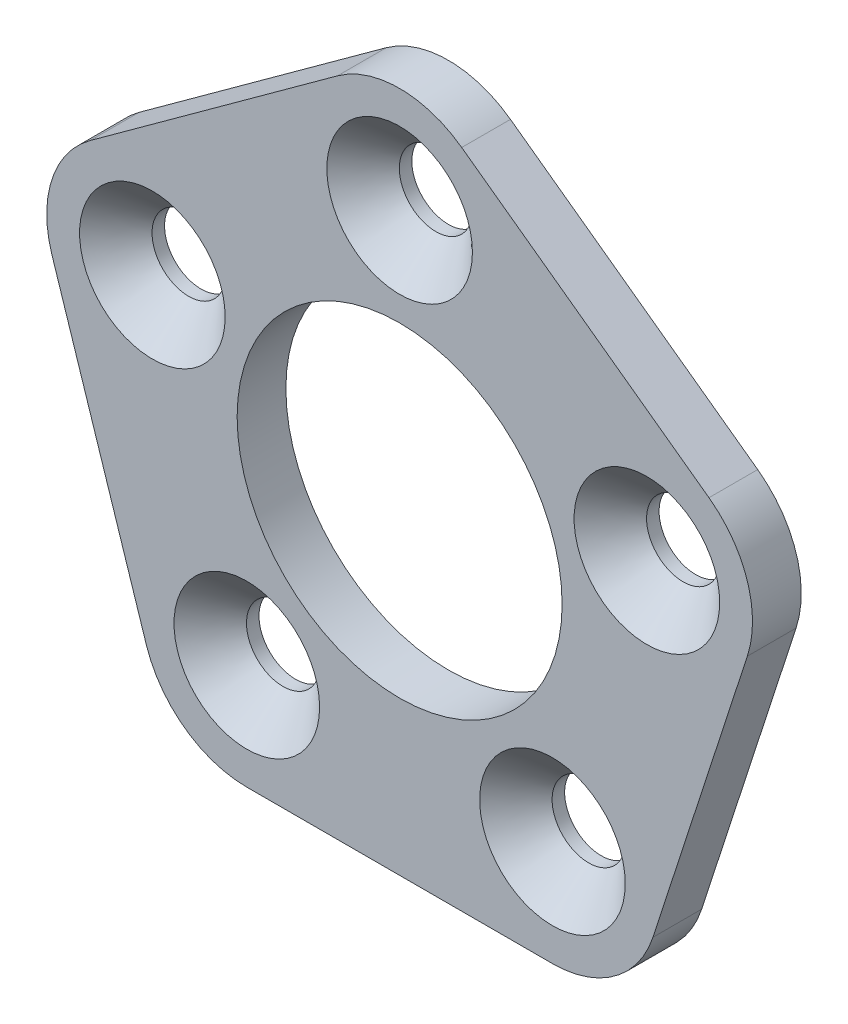
SolidWorks part; units mm, degrees
material "AISI Type A2 Tool Steel"
ref_plane "Front" through (0, 0, 0) normal (0, 0, 1) x (1, 0, 0)
ref_plane "Top" through (0, 0, 0) normal (0, 1, 0) x (1, 0, 0)
ref_plane "Right" through (0, 0, 0) normal (1, 0, 0) x (0, 0, -1)
sketch "Sketch1" plane through (0, 0, 0) normal (0, 0, 1) x (1, 0, 0)
  line L0 (-21.3988, 2.9357) -> (-15.5864, -14.9529)
  line L1 (-19.0375, 10.2029) -> (-3.8206, 21.2586)
  line L2 (-9.4046, -19.4443) -> (9.4046, -19.4443)
  line L3 (15.5864, -14.9529) -> (21.3988, 2.9357)
  line L4 (3.8206, 21.2586) -> (19.0375, 10.2029)
  circle A0 centre (0, 0) radius 16 construction
  circle A1 centre (0, 0) radius 19 construction
  circle A2 centre (0, 0) radius 10
  arc A3 (3.8206, 21.2586) -> (-3.8206, 21.2586) centre (0, 16) ccw
  arc A4 (21.3988, 2.9357) -> (19.0375, 10.2029) centre (15.2169, 4.9443) ccw
  arc A5 (9.4046, -19.4443) -> (15.5864, -14.9529) centre (9.4046, -12.9443) ccw
  arc A6 (-15.5864, -14.9529) -> (-9.4046, -19.4443) centre (-9.4046, -12.9443) ccw
  arc A7 (-19.0375, 10.2029) -> (-21.3988, 2.9357) centre (-15.2169, 4.9443) ccw
  arc A8 (-6.3645, 14.6797) -> (6.3645, 14.6797) centre (0, 16) ccw construction
  arc A9 (-15.9279, -1.5167) -> (-11.9945, 10.5893) centre (-15.2169, 4.9443) ccw construction
  arc A10 (-3.4795, -15.6171) -> (-13.7775, -8.1352) centre (-9.4046, -12.9443) ccw construction
  arc A11 (13.7775, -8.1352) -> (3.4795, -15.6171) centre (9.4046, -12.9443) ccw construction
  arc A12 (15.9279, -1.5167) -> (18.9969, -0.3436) centre (15.2169, 4.9443) ccw construction
  arc A13 (15.1668, 11.4441) -> (11.9945, 10.5893) centre (15.2169, 4.9443) ccw construction
  arc A14 (11.9945, 10.5893) -> (15.9279, -1.5167) centre (15.2169, 4.9443) ccw construction
  arc A15 (6.3645, 14.6797) -> (6.1972, 17.9609) centre (0, 16) ccw construction
  arc A16 (-6.1972, 17.9609) -> (-6.3645, 14.6797) centre (0, 16) ccw construction
  arc A17 (-3.8206, 21.2586) -> (-6.1972, 17.9609) centre (0, 16) ccw construction
  arc A18 (6.1972, 17.9609) -> (3.8206, 21.2586) centre (0, 16) ccw construction
  arc A19 (-11.9945, 10.5893) -> (-15.1668, 11.4441) centre (-15.2169, 4.9443) ccw construction
  arc A20 (-15.1668, 11.4441) -> (-19.0375, 10.2029) centre (-15.2169, 4.9443) ccw construction
  arc A21 (-21.3988, 2.9357) -> (-18.9969, -0.3436) centre (-15.2169, 4.9443) ccw construction
  arc A22 (-18.9969, -0.3436) -> (-15.9279, -1.5167) centre (-15.2169, 4.9443) ccw construction
  arc A23 (-13.7775, -8.1352) -> (-15.5708, -10.8881) centre (-9.4046, -12.9443) ccw construction
  arc A24 (-15.5708, -10.8881) -> (-15.5864, -14.9529) centre (-9.4046, -12.9443) ccw construction
  arc A25 (-5.5436, -18.1733) -> (-3.4795, -15.6171) centre (-9.4046, -12.9443) ccw construction
  arc A26 (-9.4046, -19.4443) -> (-5.5436, -18.1733) centre (-9.4046, -12.9443) ccw construction
  arc A27 (3.4795, -15.6171) -> (5.5436, -18.1733) centre (9.4046, -12.9443) ccw construction
  arc A28 (5.5436, -18.1733) -> (9.4046, -19.4443) centre (9.4046, -12.9443) ccw construction
  arc A29 (15.5864, -14.9529) -> (15.5708, -10.8881) centre (9.4046, -12.9443) ccw construction
  arc A30 (15.5708, -10.8881) -> (13.7775, -8.1352) centre (9.4046, -12.9443) ccw construction
  arc A31 (19.0375, 10.2029) -> (15.1668, 11.4441) centre (15.2169, 4.9443) ccw construction
  arc A32 (18.9969, -0.3436) -> (21.3988, 2.9357) centre (15.2169, 4.9443) ccw construction
  point P17 (0, 0)
  dimension "D1" = 32
  dimension "D2" = 38
  dimension "D3" = 20
  dimension "D4" = 13
  dimension "D5" = 5
extrude "Boss-Extrude1" add sketch "Sketch1" against normal blind 3
hole_wizard "CSK for M4 SFHCS1" positions "Sketch2" profile "Sketch4" countersink size "M4" standard "ANSI Metric"
sketch "Sketch2" plane through (0, 0, 0) normal (0, 0, 1) x (1, 0, 0)
  circle A0 centre (0, 0) radius 16 construction
  point P2 (0, 16)
  point P17 (15.2169, 4.9443)
  point P18 (9.4046, -12.9443)
  point P19 (-9.4046, -12.9443)
  point P20 (-15.2169, 4.9443)
  dimension "D1" = 5
sketch "Sketch4" plane through (0, 16, 0) normal (1, 0, 0) x (0, -1, 0)
  line L0 (0, 0) -> (0, 6.4519)
  line L1 (0, 6.4519) -> (2.25, 5.1)
  line L2 (2.25, 5.1) -> (2.25, 2.23)
  line L3 (2.25, 2.23) -> (4.48, 0)
  line L5 (4.48, 0) -> (0, 0)
  line L6 (-2.25, 2.23) -> (-4.48, 0) construction
  line L10 (0, 6.4519) -> (-2.25, 5.1) construction
  line L11 (0, -6.35) -> (0, 107.95) construction
  dimension "Hole Dia." = 4.5
  dimension "Hole Depth" = 5.1
  dimension "Near C'Sink Dia." = 8.96
  dimension "Near C'Sink Angle" = 90
  dimension "Drill Angle" = 118
